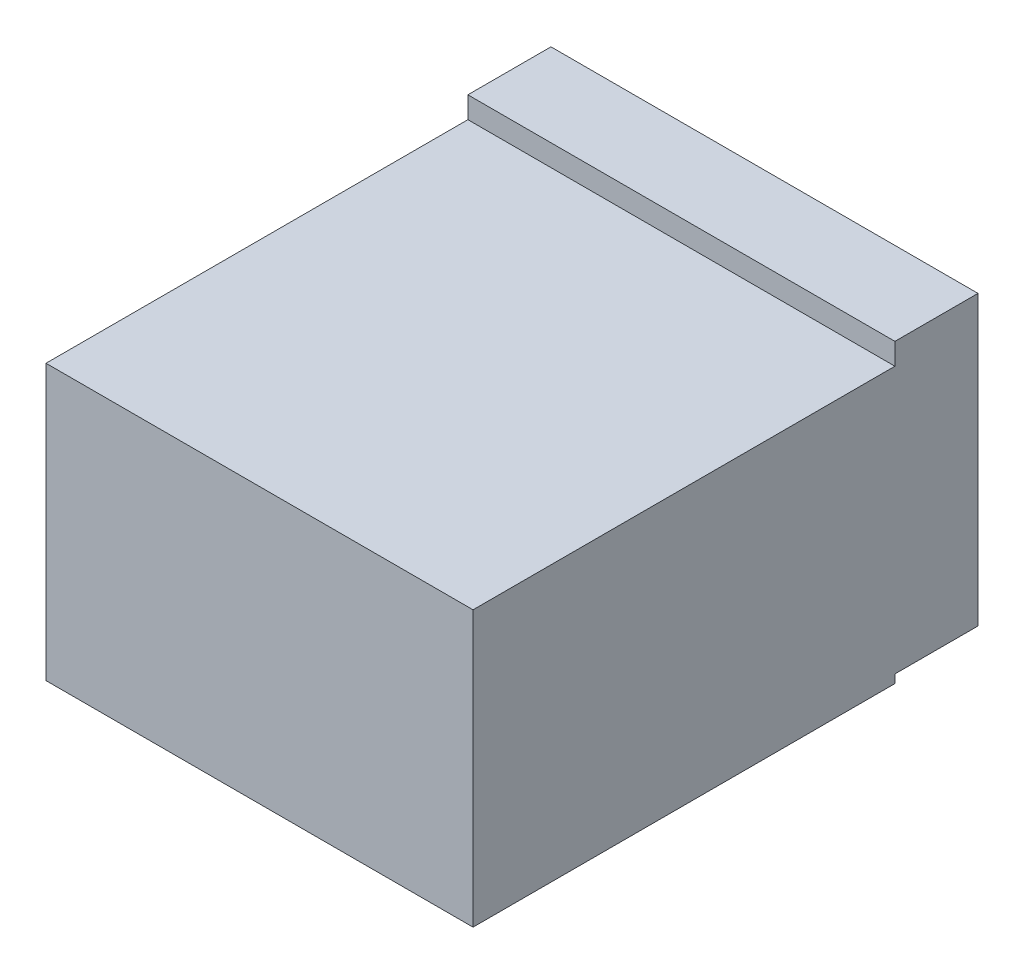
SolidWorks part; units mm, degrees
ref_plane "Front Plane" through (0, 0, 0) normal (0, 0, 1) x (1, 0, 0)
ref_plane "Top Plane" through (0, 0, 0) normal (0, 1, 0) x (1, 0, 0)
ref_plane "Right Plane" through (0, 0, 0) normal (1, 0, 0) x (0, 0, -1)
sketch "Sketch1" plane through (0, 0, 0) normal (0, 1, 0) x (1, 0, 0)
  line L0 (8.5, -15) -> (22, -15) construction
  line L1 (0, 93.6724) -> (110, 93.6724)
  line L2 (0, 93.6724) -> (0, -15)
  line L3 (0, -15) -> (110, -15)
  line L4 (110, 93.6724) -> (110, -15)
  line L5 (0, 87) -> (0, 0) construction
  line L6 (110, 0) -> (110, 87) construction
extrude "SCROD-and-carriers-and-HV" add sketch "Sketch1" along normal up to surface (57.8026 mm away) and the other way up to surface (13 mm away)
sketch "Sketch2" plane through (0, 0, -93.6724) normal (0, 0, -1) x (-1, 0, 0)
  line L0 (0, 57.8026) -> (0, -13) construction
  line L1 (0, -10.8474) -> (-110, -10.8474)
  line L2 (0, -10.8474) -> (0, 63.3526)
  line L3 (0, 63.3526) -> (-110, 63.3526)
  line L4 (-110, -10.8474) -> (-110, 63.3526)
  line L5 (-3.9131, -10.8474) -> (-50.0869, -10.8474) construction
  line L7 (-110, 57.8026) -> (-110, -13) construction
  line L8 (-52.75, 63.3526) -> (-1.25, 63.3526) construction
extrude "pmt-assembly" add sketch "Sketch2" along normal up to surface (21.4016 mm away)
